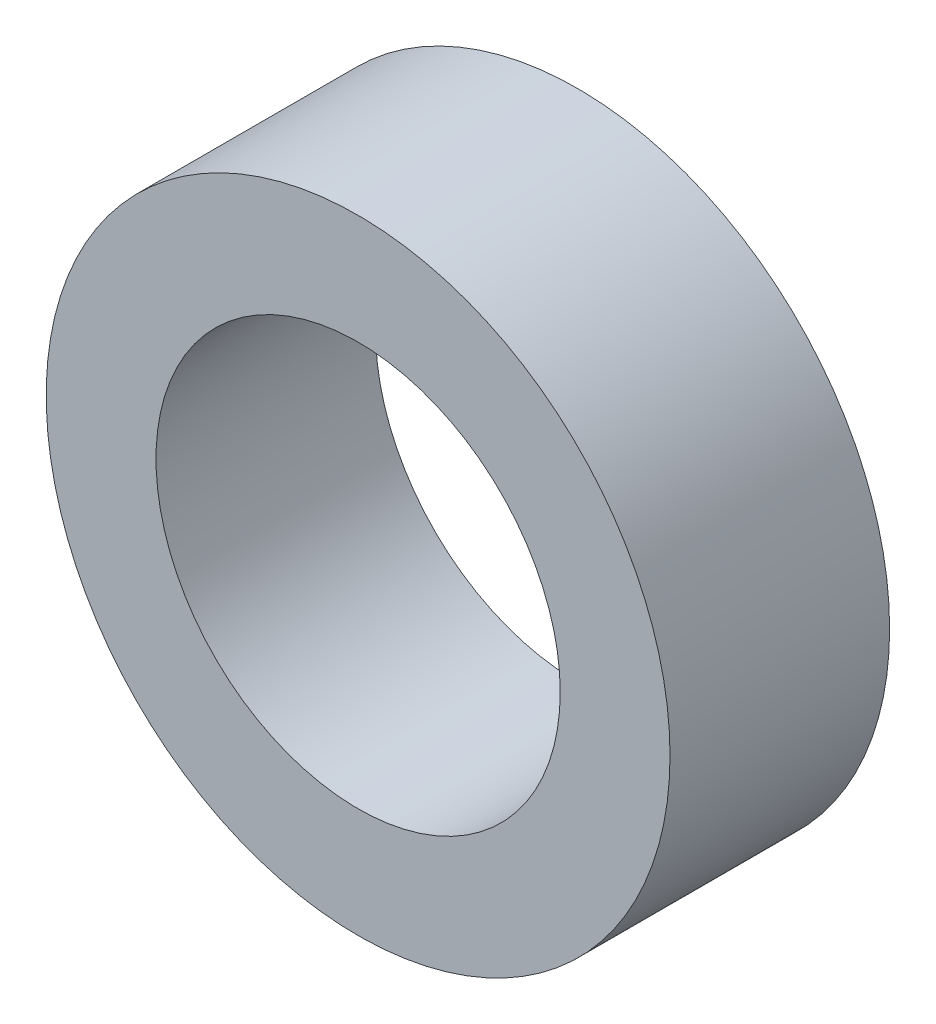
SolidWorks part; units mm, degrees
material "ABS"
ref_plane "Front" through (0, 0, 0) normal (0, 0, 1) x (1, 0, 0)
ref_plane "Top" through (0, 0, 0) normal (0, 1, 0) x (1, 0, 0)
ref_plane "Right" through (0, 0, 0) normal (1, 0, 0) x (0, 0, -1)
sketch "Sketch1" plane through (0, 0, 0) normal (0, 0, 1) x (1, 0, 0)
  circle A0 centre (0, 0) radius 5.1435
  circle A1 centre (0, 0) radius 7.9375
  dimension "D1" = 10.287
  dimension "D2" = 15.875
extrude "Boss-Extrude1" add sketch "Sketch1" along normal blind 5.588
